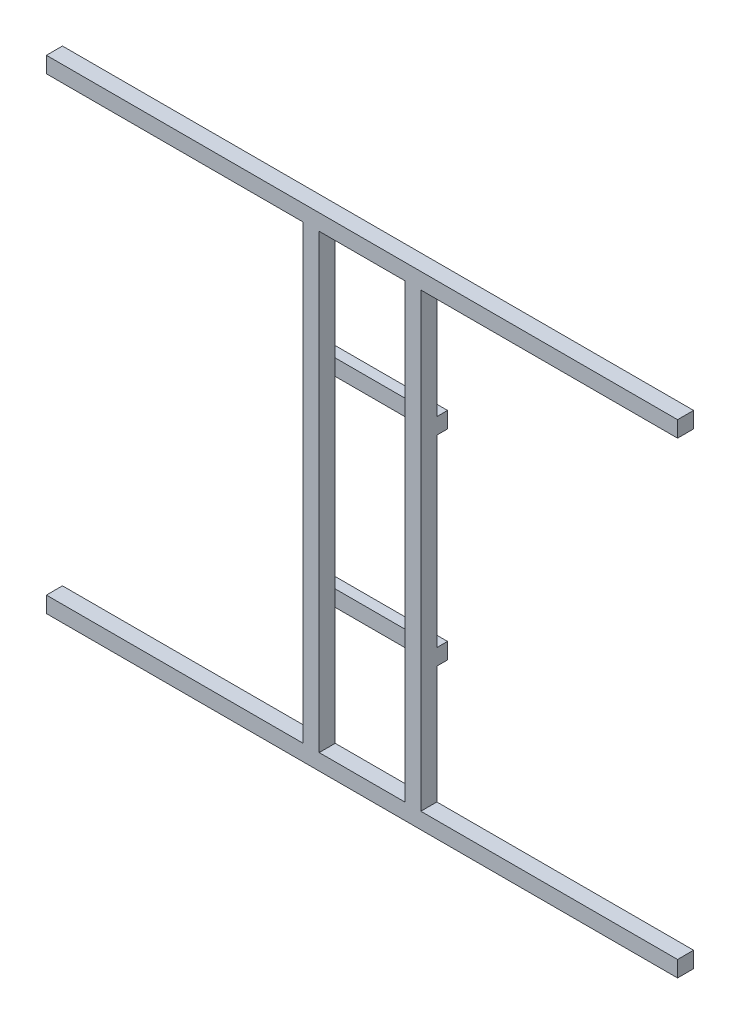
SolidWorks part; units mm, degrees
ref_plane "前视基准面" through (0, 0, 0) normal (0, 0, 1) x (1, 0, 0)
ref_plane "上视基准面" through (0, 0, 0) normal (0, 1, 0) x (1, 0, 0)
ref_plane "右视基准面" through (0, 0, 0) normal (1, 0, 0) x (0, 0, -1)
sketch "Sketch1" plane through (0, 0, 0) normal (0, 0, 1) x (1, 0, 0)
  line L0 (57, 0) -> (129.8959, 0) construction
  line L1 (57, 54.0142) -> (57, -54.0142) construction
  line L2 (85, 100.4999) -> (85, 76) construction
  line L3 (55, 100.9999) -> (-55, 100.9999)
  line L4 (55, 100.9999) -> (55, 85.9999)
  line L5 (55, 85.9999) -> (-55, 85.9999)
  line L6 (-55, 100.9999) -> (-55, 85.9999)
  line L7 (-85, 76) -> (-85, 100.4999) construction
  line L8 (-55, -100.9999) -> (-55, -85.9999)
  line L9 (55, -85.9999) -> (-55, -85.9999)
  line L10 (55, -100.9999) -> (55, -85.9999)
  line L11 (55, -100.9999) -> (-55, -100.9999)
  circle A0 centre (35, 93.4999) radius 2.1 construction
  dimension "D2" = 7.5
  dimension "D1" = 15
  dimension "D3" = 30
  dimension "D4" = 30
extrude "Extrude1" add sketch "Sketch1" along normal blind 10
sketch "Sketch2" plane through (0, 0, 10) normal (0, 0, 1) x (1, 0, 0)
  line L0 (55, -100.9999) -> (55, -85.9999) construction
  line L2 (55, -210.9999) -> (55, 210.9999)
  line L4 (40, -210.9999) -> (40, 210.9999)
  line L6 (-55, -210.9999) -> (-55, 210.9999)
  line L8 (-40, -210.9999) -> (-40, 210.9999)
  line L9 (-55, -85.9999) -> (-55, -100.9999) construction
  line L12 (-40, 210.9999) -> (40, 210.9999)
  line L13 (-295, -210.9999) -> (-55, -210.9999)
  line L14 (-295, -210.9999) -> (-295, -225.9999)
  line L15 (-295, -225.9999) -> (295, -225.9999)
  line L16 (295, -210.9999) -> (295, -225.9999)
  line L17 (-295, 210.9999) -> (-55, 210.9999)
  line L18 (-295, 210.9999) -> (-295, 225.9999)
  line L19 (-295, 225.9999) -> (295, 225.9999)
  line L20 (295, 210.9999) -> (295, 225.9999)
  line L21 (55, 210.9999) -> (295, 210.9999)
  line L22 (55, -210.9999) -> (295, -210.9999)
  line L23 (-40, -210.9999) -> (40, -210.9999)
  dimension "D1" = 15
  dimension "D2" = 15
  dimension "D5" = 590
  dimension "D6" = 240
  dimension "D7" = 15
  dimension "D8" = 15
extrude "Extrude2" add sketch "Sketch2" along normal blind 15
